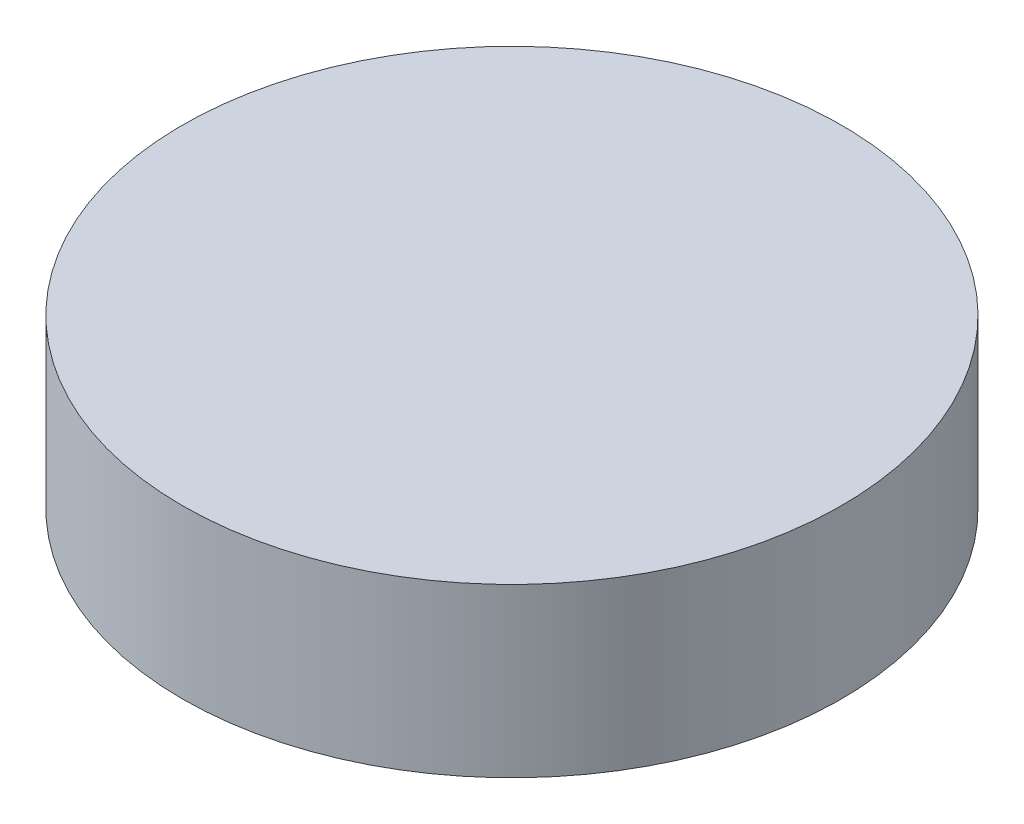
SolidWorks part; units mm, degrees
ref_plane "Front Plane" through (0, 0, 0) normal (0, 0, 1) x (1, 0, 0)
ref_plane "Top Plane" through (0, 0, 0) normal (0, 1, 0) x (1, 0, 0)
ref_plane "Right Plane" through (0, 0, 0) normal (1, 0, 0) x (0, 0, -1)
sketch "Sketch1" plane through (0, 0, 0) normal (0, 1, 0) x (1, 0, 0)
  circle A0 centre (0, 0) radius 5
  dimension "D1" = 10
extrude "Boss-Extrude1" add sketch "Sketch1" along normal blind 2.54
